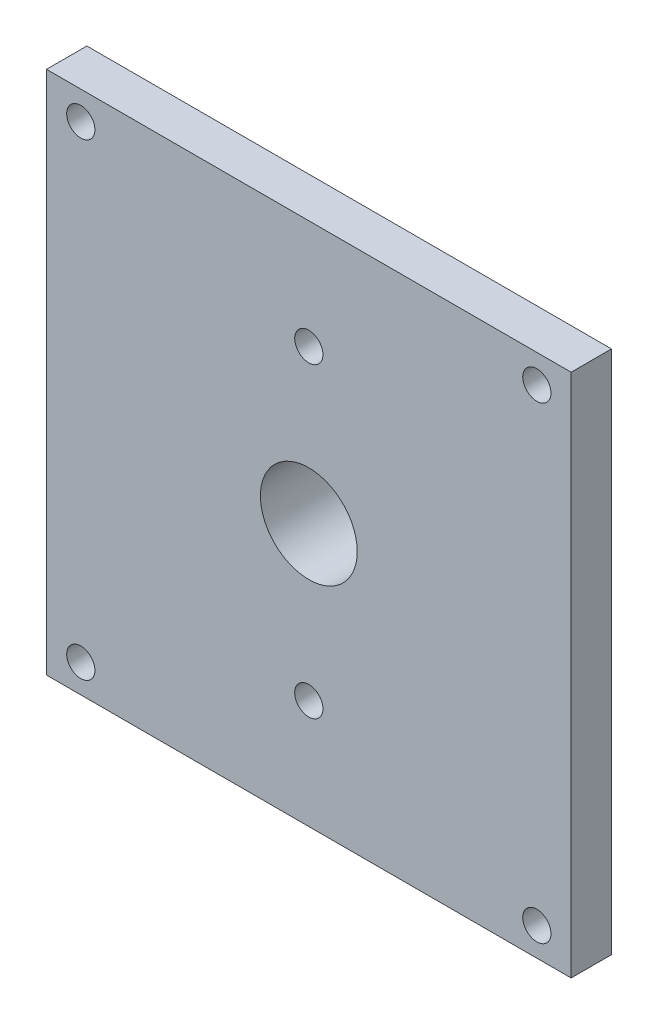
SolidWorks part; units mm, degrees
ref_plane "Front Plane" through (0, 0, 0) normal (0, 0, 1) x (1, 0, 0)
ref_plane "Top Plane" through (0, 0, 0) normal (0, 1, 0) x (1, 0, 0)
ref_plane "Right Plane" through (0, 0, 0) normal (1, 0, 0) x (0, 0, -1)
sketch "Sketch1" plane through (0, 0, 0) normal (0, 0, 1) x (1, 0, 0)
  circle A0 centre (0, 0) radius 15
  dimension "D1" = 30
extrude "Boss-Extrude1" add sketch "Sketch1" against normal blind 20
sketch "Sketch2" plane through (0, 0, -20) normal (0, 0, -1) x (-1, 0, 0)
  circle A0 centre (0, 0) radius 8
  dimension "D1" = 16
extrude "Cut-Extrude1" cut sketch "Sketch2" against normal blind 5
sketch "Sketch4" plane through (0, 0, 0) normal (0, 0, 1) x (1, 0, 0)
  line L1 (-32.5, 32.5) -> (32.5, 32.5)
  line L2 (-32.5, 32.5) -> (-32.5, -32.5)
  line L3 (-32.5, -32.5) -> (32.5, -32.5)
  line L4 (32.5, 32.5) -> (32.5, -32.5)
  line L5 (-32.5, 32.5) -> (32.5, -32.5) construction
  line L6 (-32.5, -32.5) -> (32.5, 32.5) construction
  point P0 (0, 0)
  dimension "D1" = 65
  dimension "D2" = 65
extrude "Boss-Extrude2" add sketch "Sketch4" against normal blind 5
sketch "Sketch3" plane through (0, 0, 0) normal (0, 0, 1) x (1, 0, 0)
  circle A0 centre (0, 0) radius 6
  dimension "D1" = 12
extrude "Cut-Extrude2" cut sketch "Sketch3" against normal through all
sketch "Sketch5" plane through (0, 0, -5) normal (0, 0, -1) x (-1, 0, 0)
  line L3 (0, 0) -> (0, -3.3136) construction
  line L4 (0, 0) -> (3.2444, 0) construction
  circle A0 centre (-28.25, 29) radius 1.75
  circle A1 centre (28.25, 29) radius 1.75
  circle A2 centre (28.25, -29) radius 1.75
  circle A3 centre (-28.25, -29) radius 1.75
  dimension "D1" = 3.5
  dimension "D2" = 28.25
  dimension "D3" = 29
extrude "Cut-Extrude3" cut sketch "Sketch5" against normal through all
sketch "Sketch6" plane through (0, 0, 0) normal (0, 0, 1) x (1, 0, 0)
  line L0 (-3.8435, 0) -> (0, 0) construction
  circle A0 centre (0, 19) radius 1.75
  circle A1 centre (0, -19) radius 1.75
  dimension "D1" = 3.5
  dimension "D2" = 19
extrude "Cut-Extrude4" cut sketch "Sketch6" against normal through all
